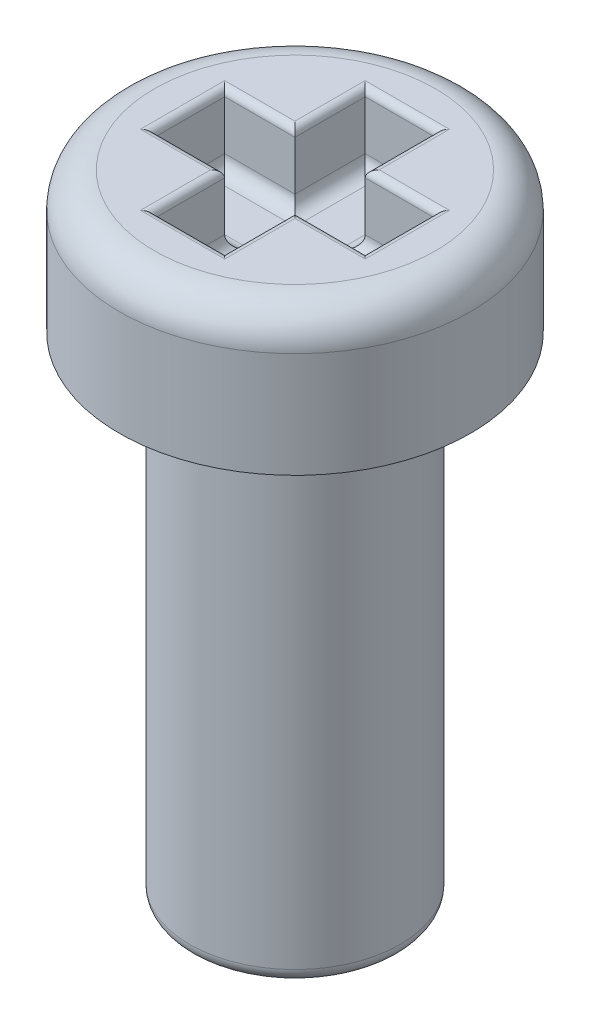
SolidWorks part; units mm, degrees
ref_plane "Front Plane" through (0, 0, 0) normal (0, 0, 1) x (1, 0, 0)
ref_plane "Top Plane" through (0, 0, 0) normal (0, 1, 0) x (1, 0, 0)
ref_plane "Right Plane" through (0, 0, 0) normal (1, 0, 0) x (0, 0, -1)
sketch "Sketch1" plane through (0, 0, 0) normal (0, 1, 0) x (1, 0, 0)
  circle A0 centre (0, 0) radius 1.5
  dimension "D1" = 3
extrude "Boss-Extrude1" add sketch "Sketch1" along normal blind 7
fillet "Fillet1" radius 0.2 1 edges at (0, 0, 1.5)
sketch "Sketch2" plane through (0, 0, 0) normal (0, 0, 1) x (1, 0, 0)
  line L0 (0, 0) -> (0, 13.199) construction
  line L1 (0, 7) -> (-2.5, 7)
  line L2 (1.5, 7) -> (-1.5, 7) construction
  line L3 (-2.5, 7) -> (-2.5, 9)
  line L4 (-2.5, 9) -> (0, 9)
  line L5 (0, 9) -> (0, 7)
  dimension "D1" = 2
  dimension "D2" = 2.5
revolve "Revolve1" add sketch "Sketch2" angle 360 about L0
sketch "Sketch3" plane through (0, 9, 0) normal (0, 1, 0) x (1, 0, 0)
  line L0 (0, -1003) -> (0, -1.5) construction
  line L1 (-1003, 0) -> (-1.5, 0) construction
  line L2 (-0.5, 0.5) -> (-1.5, 0.5)
  line L3 (-0.5, 1.5) -> (0.5, 1.5)
  line L4 (-0.5, 1.5) -> (-0.5, 0.5)
  line L5 (-0.5, -1.5) -> (0.5, -1.5)
  line L6 (0.5, 1.5) -> (0.5, 0.5)
  line L7 (0, -0.5) -> (0, 1.5) construction
  line L8 (-0.5, 0) -> (0.5, 0) construction
  line L9 (1.5, 0.5) -> (0.5, 0.5)
  line L10 (1.5, 0.5) -> (1.5, -0.5)
  line L11 (1.5, -0.5) -> (0.5, -0.5)
  line L12 (-1.5, 0.5) -> (-1.5, -0.5)
  line L13 (0, -0.5) -> (0, 0.5) construction
  line L14 (0.5, 0) -> (-0.5, 0) construction
  line L15 (-0.5, -0.5) -> (-0.5, -1.5)
  line L16 (-0.5, 0) -> (0.5, 0) construction
  line L17 (-0.5, -0.5) -> (-1.5, -0.5)
  line L18 (0, -0.5) -> (0, 50000) construction
  line L19 (0.5, -0.5) -> (0.5, -1.5)
  line L20 (1.5, 0) -> (50000, 0) construction
  point P5 (0, 0)
  point P9 (0, 0)
  dimension "D1" = 1
  dimension "D2" = 1
  dimension "D3" = 1
  dimension "D4" = 1
extrude "Cut-Extrude1" cut sketch "Sketch3" against normal blind 1
fillet "Fillet3" radius 0.1 12 edges at (-1, 9, 0.5) (-0.5, 9, 1) (0, 9, 1.5) (0.5, 9, 1) (1, 9, 0.5) (1.5, 9, 0) (1, 9, -0.5) (0.5, 9, -1) (0, 9, -1.5) (-0.5, 9, -1) (-1, 9, -0.5) (-1.5, 9, 0)
fillet "Fillet4" radius 0.2 12 edges at (-1, 8, -0.5) (-1.5, 8, 0) (-1, 8, 0.5) (-0.5, 8, 1) (0.5, 8, 1) (0, 8, 1.5) (1, 8, 0.5) (1.5, 8, 0) (1, 8, -0.5) (0.5, 8, -1) (0, 8, -1.5) (-0.5, 8, -1)
fillet "Fillet5" radius 0.5 1 edges at (0, 9, -2.5)
